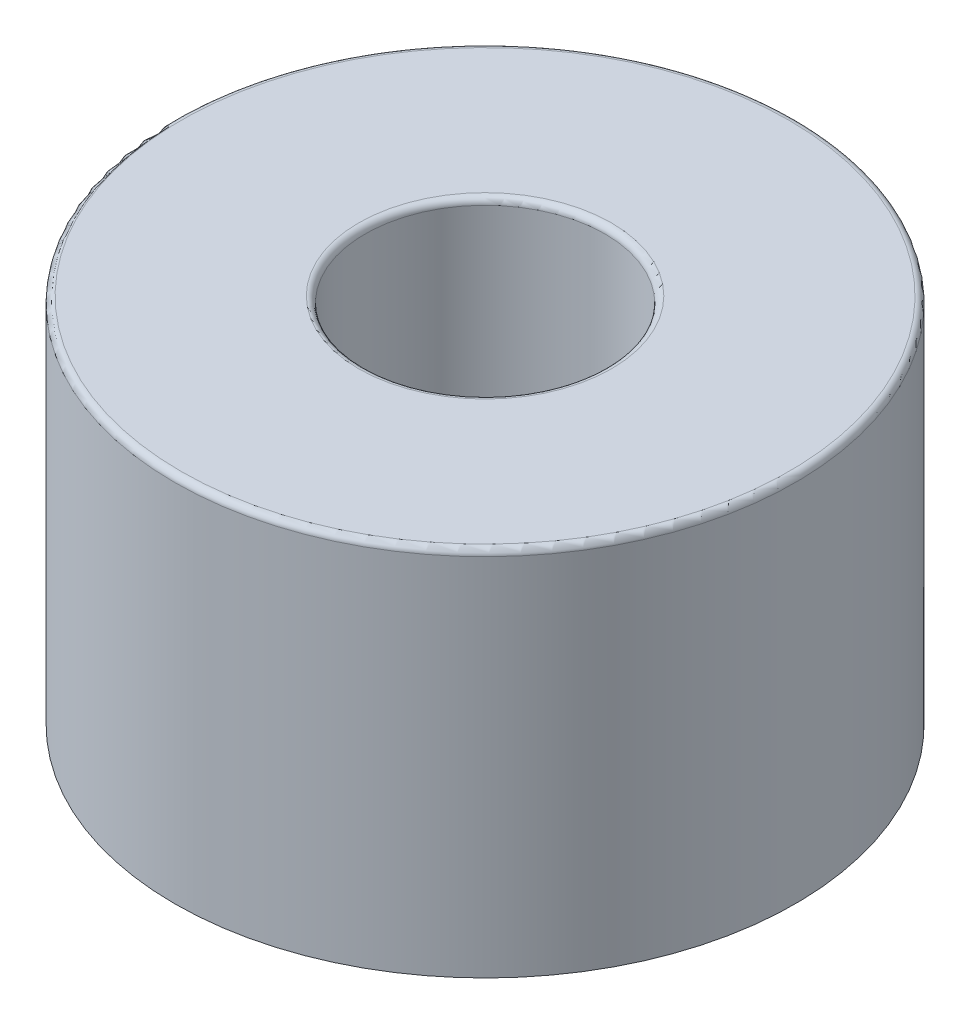
SolidWorks part; units mm, degrees
material "POLYURETHANE (11671)"
ref_plane "Front" through (0, 0, 0) normal (0, 0, 1) x (1, 0, 0)
ref_plane "Top" through (0, 0, 0) normal (0, 1, 0) x (1, 0, 0)
ref_plane "Right" through (0, 0, 0) normal (1, 0, 0) x (0, 0, -1)
sketch "Sketch1" plane through (0, 0, 0) normal (0, 1, 0) x (1, 0, 0)
  circle A0 centre (0, 0) radius 4.7625
  circle A1 centre (0, 0) radius 12.319
  dimension "D1" = 9.525
  dimension "D2" = 24.638
extrude "Boss-Extrude1" add sketch "Sketch1" along normal blind 14.732
fillet "Fillet1" radius 0.254 2 edges at (0, 14.732, 4.7625) (0, 14.732, 12.319)
